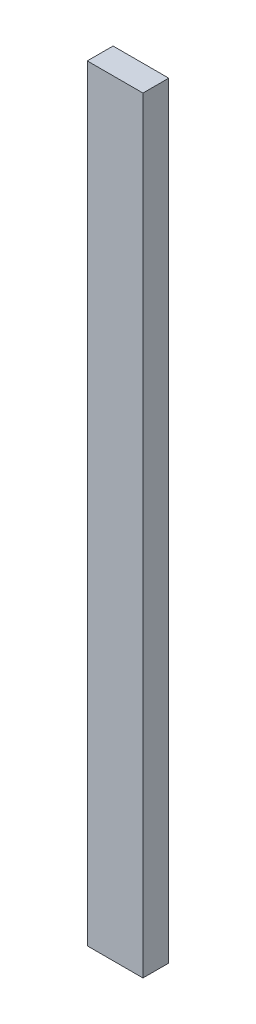
SolidWorks part; units mm, degrees
ref_plane "Front Plane" through (0, 0, 0) normal (0, 0, 1) x (1, 0, 0)
ref_plane "Top Plane" through (0, 0, 0) normal (0, 1, 0) x (1, 0, 0)
ref_plane "Right Plane" through (0, 0, 0) normal (1, 0, 0) x (0, 0, -1)
sketch "Sketch1" plane through (0, 0, 0) normal (0, 0, 1) x (1, 0, 0)
  line L0 (-0.889, 14.859) -> (1.27, 14.859)
  line L1 (1.27, 14.859) -> (1.27, -14.859)
  line L2 (1.27, -14.859) -> (-0.889, -14.859)
  line L3 (-0.889, -14.859) -> (-0.889, 14.859)
extrude "Component_Outline" add sketch "Sketch1" along normal blind 1 separate body
sketch3d "3DSketch1"
  line L0 (0, 0, 0) -> (1, 0, 0)
  line L1 (0, 0, 0) -> (0, 1, 0)
  line L2 (0, 0, 0) -> (0, 0, 1)
  point P0 (0, 0, 0)
